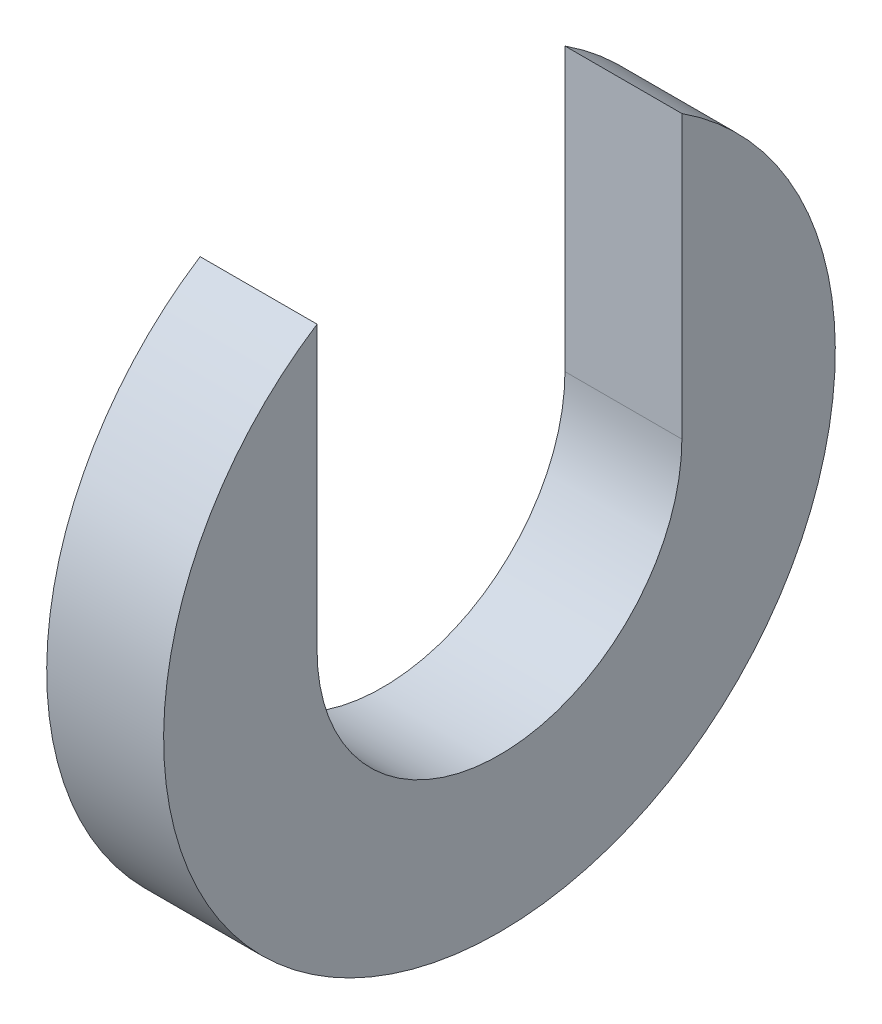
SolidWorks part; units mm, degrees
ref_plane "Front Plane" through (0, 0, 0) normal (0, 0, 1) x (1, 0, 0)
ref_plane "Top Plane" through (0, 0, 0) normal (0, 1, 0) x (1, 0, 0)
ref_plane "Right Plane" through (0, 0, 0) normal (1, 0, 0) x (0, 0, -1)
sketch "Sketch2" plane through (0, 0, 0) normal (1, 0, 0) x (0, 0, -1)
  line L0 (-4.953, 0) -> (-4.953, 7.6562)
  line L1 (4.953, 0) -> (4.953, 7.6562)
  arc A0 (-4.953, 7.6562) -> (4.953, 7.6562) centre (0, 0) ccw
  arc A2 (-4.953, 0) -> (4.953, 0) centre (0, 0) ccw
  dimension "D1" = 9.906
  dimension "D2" = 18.2372
extrude "Boss-Extrude1" add sketch "Sketch2" along normal blind 3.175
